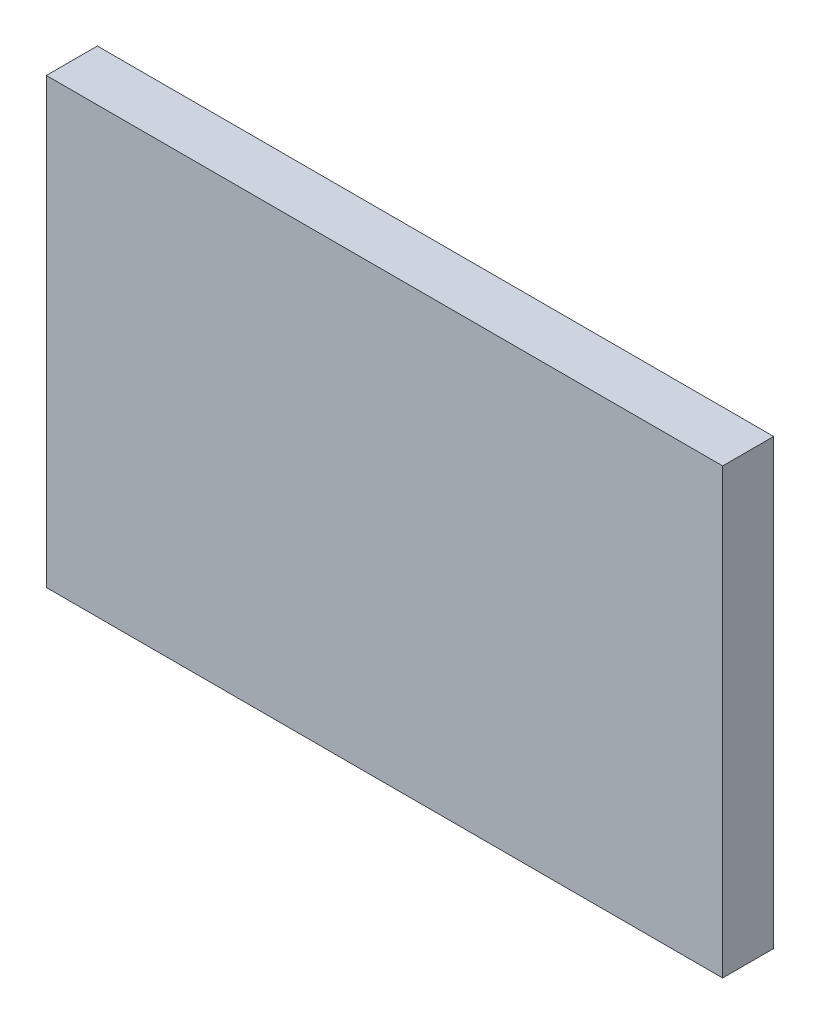
SolidWorks part; units mm, degrees
material "ABS PC"
ref_plane "Front Plane" through (0, 0, 0) normal (0, 0, 1) x (1, 0, 0)
ref_plane "Top Plane" through (0, 0, 0) normal (0, 1, 0) x (1, 0, 0)
ref_plane "Right Plane" through (0, 0, 0) normal (1, 0, 0) x (0, 0, -1)
sketch "Sketch1" plane through (0, 0, 0) normal (0, 0, 1) x (1, 0, 0)
  line L1 (0, 0) -> (38.735, 0)
  line L2 (0, 0) -> (0, 25.4)
  line L3 (0, 25.4) -> (38.735, 25.4)
  line L4 (38.735, 0) -> (38.735, 25.4)
  dimension "D1" = 25.4
  dimension "D2" = 38.735
extrude "Boss-Extrude1" add sketch "Sketch1" against normal blind 2.921
